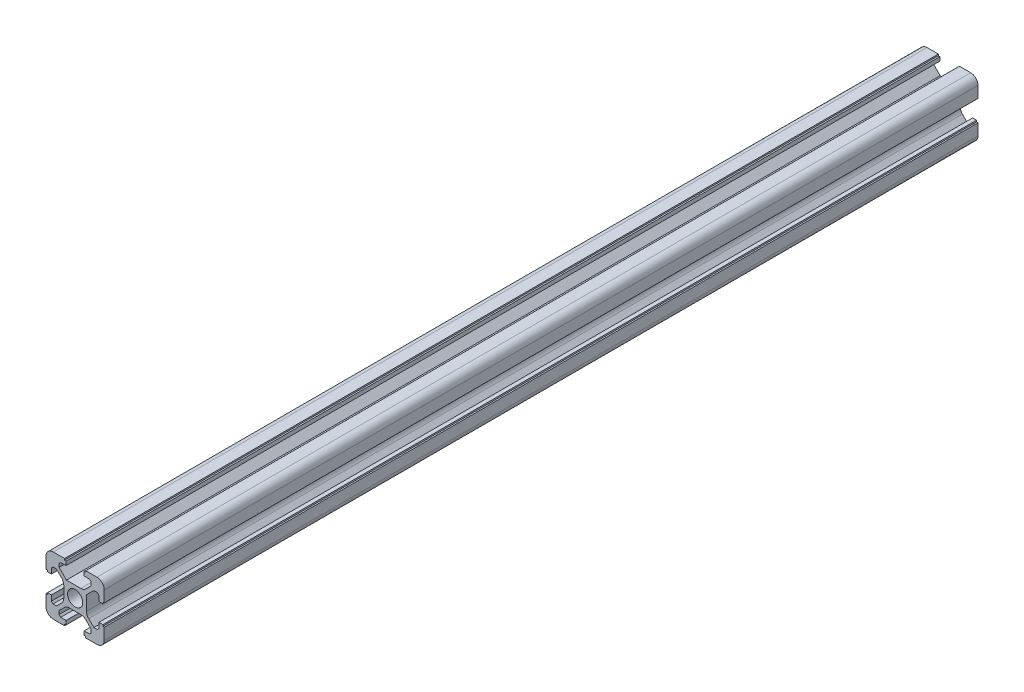
SolidWorks part; units mm, degrees
material "6061 Alloy"
ref_plane "Front Plane" through (0, 0, 0) normal (0, 0, 1) x (1, 0, 0)
ref_plane "Top Plane" through (0, 0, 0) normal (0, 1, 0) x (1, 0, 0)
ref_plane "Right Plane" through (0, 0, 0) normal (1, 0, 0) x (0, 0, -1)
sketch "Sketch1" plane through (0, 0, 0) normal (0, 0, 1) x (1, 0, 0)
  line L0 (-3.1, 10) -> (3.1, 10)
  line L1 (-10, 10) -> (10, 10)
  line L2 (-10, 10) -> (-10, -10)
  line L3 (-10, -10) -> (10, -10)
  line L4 (10, 10) -> (10, -10)
  line L5 (-10, 10) -> (10, -10) construction
  line L6 (-10, -10) -> (10, 10) construction
  line L7 (-5.5, 5.5) -> (5.5, 5.5)
  line L8 (-5.5, 5.5) -> (-5.5, -5.5)
  line L9 (-5.5, -5.5) -> (5.5, -5.5)
  line L10 (5.5, 5.5) -> (5.5, -5.5)
  line L11 (-5.5, 5.5) -> (5.5, -5.5) construction
  line L12 (-5.5, -5.5) -> (5.5, 5.5) construction
  line L13 (-8.15, -8.15) -> (8.15, -8.15)
  line L14 (-8.15, -8.15) -> (-8.15, 8.15)
  line L15 (-8.15, 8.15) -> (8.15, 8.15)
  line L16 (8.15, -8.15) -> (8.15, 8.15)
  line L17 (-8.15, -8.15) -> (8.15, 8.15) construction
  line L18 (-8.15, 8.15) -> (8.15, -8.15) construction
  line L19 (10, 3.1) -> (8.15, 3.1)
  line L20 (-3.1, 10) -> (3.1, 10)
  line L21 (-3.1, 10) -> (-3.1, 8.15)
  line L22 (-3.1, 8.15) -> (3.1, 8.15)
  line L23 (3.1, 10) -> (3.1, 8.15)
  line L24 (10, -3.1) -> (8.15, -3.1)
  line L25 (3.1, -10) -> (3.1, -8.15)
  line L26 (-3.1, -10) -> (-3.1, -8.15)
  line L27 (-10, -3.1) -> (-8.15, -3.1)
  line L28 (-10, 3.1) -> (-8.15, 3.1)
  circle A0 centre (0, 0) radius 2.6
  point P0 (0, 0)
  point P19 (0, 10)
  point P36 (0, 0)
  dimension "D3" = 5.2
  dimension "D1" = 20
  dimension "D2" = 20
  dimension "D4" = 11
  dimension "D5" = 11
  dimension "D6" = 1.85
  dimension "D7" = 1.85
  dimension "D8" = 6.2
  dimension "D9" = 4
extrude "Boss-Extrude1" add sketch "Sketch1" along normal blind 300 contours L2 L28 L14 L15 L21 L1 | L1 L23 L15 L16 L19 L4 | L13 L16 L15 L14 L7 L10 L9 L8 | L25 L3 L4 L24 L16 L13 | L27 L2 L3 L26 L13 L14 | L10 L7 L8 L9 A0
sketch "Sketch2" plane through (0, 0, 300) normal (0, 0, 1) x (1, 0, 0)
  line L0 (-10, 10) -> (-3.1, 10) construction
  line L1 (-3.9, 3.9) -> (3.9, 3.9)
  line L2 (-3.9, 3.9) -> (-3.9, -3.9)
  line L3 (-3.9, -3.9) -> (3.9, -3.9)
  line L4 (3.9, 3.9) -> (3.9, -3.9)
  line L5 (-3.9, 3.9) -> (3.9, -3.9) construction
  line L6 (-3.9, -3.9) -> (3.9, 3.9) construction
  line L7 (-10, -3.1) -> (-10, -10) construction
  line L8 (8.15, 5.5) -> (8.15, -5.5)
  line L9 (-5.5, -8.15) -> (5.5, -8.15)
  line L10 (-5.5, -8.15) -> (-5.5, 8.15)
  line L11 (-5.5, 8.15) -> (5.5, 8.15)
  line L12 (5.5, -8.15) -> (5.5, 8.15)
  line L13 (-5.5, -8.15) -> (5.5, 8.15) construction
  line L14 (-5.5, 8.15) -> (5.5, -8.15) construction
  line L15 (-8.15, 5.5) -> (8.15, 5.5)
  line L16 (-8.15, -5.5) -> (8.15, -5.5)
  line L17 (-8.15, 5.5) -> (-8.15, -5.5)
  line L18 (5.5, -8.15) -> (-5.5, -8.15)
  line L19 (5.5, 8.15) -> (5.5, -8.15)
  line L20 (-5.5, 8.15) -> (-5.5, -8.15)
  line L21 (5.5, 8.15) -> (-5.5, 8.15)
  line L22 (-8.15, -5.5) -> (-8.15, 5.5)
  line L23 (8.15, -5.5) -> (-8.15, -5.5)
  line L24 (8.15, 5.5) -> (-8.15, 5.5)
  line L25 (8.15, -5.5) -> (8.15, 5.5)
  line L26 (-10, 3.1) -> (-3.1, 10)
  line L27 (-6.55, 6.55) -> (-3.9, 3.9)
  line L28 (-6.0904, 7.0096) -> (-7.0096, 6.0904)
  line L29 (-7.0096, 6.0904) -> (-3.9, 2.9808)
  line L30 (-6.0904, 7.0096) -> (-2.9808, 3.9)
  line L31 (6.0904, 7.0096) -> (2.9808, 3.9)
  line L32 (7.0096, 6.0904) -> (3.9, 2.9808)
  line L33 (3.1, 10) -> (10, 3.1)
  line L34 (7.0096, -6.0904) -> (3.9, -2.9808)
  line L35 (6.0904, -7.0096) -> (2.9808, -3.9)
  line L36 (10, -3.1) -> (3.1, -10)
  line L37 (-6.0904, -7.0096) -> (-2.9808, -3.9)
  line L38 (-7.0096, -6.0904) -> (-3.9, -2.9808)
  line L39 (-3.1, -10) -> (-10, -3.1)
  point P0 (0, 0)
  point P10 (0, 0)
  point P19 (0, 0)
  point P24 (0, 0)
  point P29 (0, 0)
  point P34 (0, 0)
  point P40 (-6.55, 6.55)
  point P63 (0, 0)
  line M8 (-3.1, -8.15) -> (3.1, -8.15)
  line M13 (8.15, -3.1) -> (8.15, 3.1)
  line M18 (3.1, 8.15) -> (-3.1, 8.15)
  line M23 (-8.15, 3.1) -> (-8.15, -3.1)
  dimension "D1" = 6.1
  dimension "D2" = 6.1
  dimension "D3" = 11
  dimension "D4" = 1.85
  dimension "D6" = 1.3
  dimension "D7" = 90
  dimension "D8" = 90
  dimension "D5" = 4
  dimension "D9" = 4
extrude "Cut-Extrude2" cut sketch "Sketch2" against normal through all contours L39 L23 L38 L20 L29 L24 L26 L22 L17 M23 | L20 L38 L2 L29 | L33 L11 L21 L26 L20 L30 L24 L31 L19 M18 | L31 L24 L30 L1 | L36 L8 L25 L33 L24 L32 L19 L34 L23 M13 | L34 L19 L32 L4 | L39 L18 L9 L36 L19 L35 L23 L37 L20 M8 | L37 L23 L35 L3
fillet "Fillet1" radius 2.5 4 edges at (10, 10, 150) (-10, -10, 150) (10, -10, 150) (-10, 10, 150)
fillet "Fillet2" radius 2.5 6 edges at (3.9, -2.9808, 150) (2.9808, -3.9, 150) (-2.9808, -3.9, 150) (-3.9, -2.9808, 150) (-3.9, 2.9808, 150) (2.9808, 3.9, 150)
sketch "Sketch3" plane through (0, 0, 300) normal (0, 0, 1) x (1, 0, 0)
  line L0 (0, 0) -> (0, 10) construction
  line L1 (-3.1, 10) -> (3.1, 10) construction
  line L2 (9.5, 3.625) -> (9.5, -3.625)
  line L3 (-3.625, 9.5) -> (3.625, 9.5)
  line L4 (-3.625, 9.5) -> (-3.625, 10.5)
  line L5 (-3.625, 10.5) -> (3.625, 10.5)
  line L6 (3.625, 9.5) -> (3.625, 10.5)
  line L7 (-3.625, 9.5) -> (3.625, 10.5) construction
  line L8 (-3.625, 10.5) -> (3.625, 9.5) construction
  line L9 (9.5, -3.625) -> (10.5, -3.625)
  line L10 (10.5, 3.625) -> (10.5, -3.625)
  line L11 (9.5, 3.625) -> (10.5, 3.625)
  line L12 (3.625, -9.5) -> (-3.625, -9.5)
  line L13 (-3.625, -9.5) -> (-3.625, -10.5)
  line L14 (3.625, -10.5) -> (-3.625, -10.5)
  line L15 (3.625, -9.5) -> (3.625, -10.5)
  line L16 (-9.5, -3.625) -> (-9.5, 3.625)
  line L17 (-9.5, 3.625) -> (-10.5, 3.625)
  line L18 (-10.5, -3.625) -> (-10.5, 3.625)
  line L19 (-9.5, -3.625) -> (-10.5, -3.625)
  point P26 (0, 0)
  dimension "D1" = 1
  dimension "D2" = 7.25
  dimension "D3" = 4
extrude "Cut-Extrude3" cut sketch "Sketch3" against normal through all
